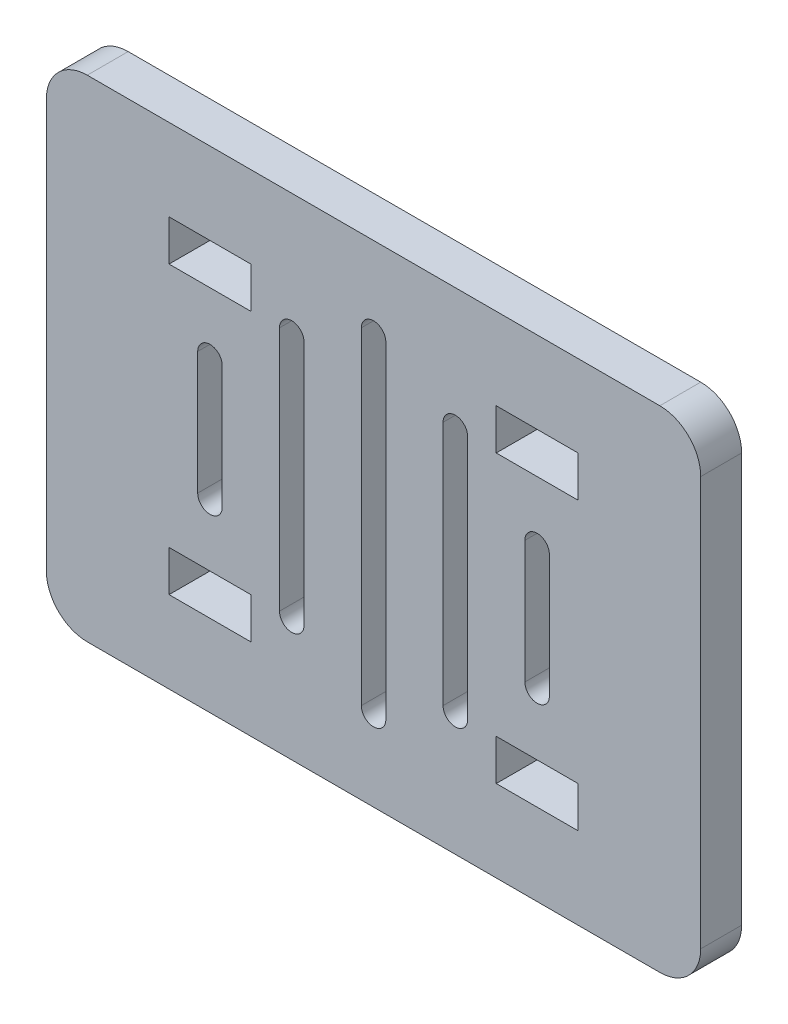
SolidWorks part; units mm, degrees
ref_plane "Front Plane" through (0, 0, 0) normal (1, 0, 0) x (0, 1, 0)
ref_plane "Top Plane" through (0, 0, 0) normal (0, 0, 1) x (0, 1, 0)
ref_plane "Right Plane" through (0, 0, 0) normal (0, 1, 0) x (-1, 0, 0)
sketch "Sketch1" plane through (0, 0, 0) normal (0, 0, 1) x (0, 1, 0)
  line L0 (0, 0) -> (0, 40) construction
  line L1 (0, -0.75) -> (0, 0)
  line L2 (-15, 0) -> (15, 0) construction
  line L3 (15, -5) -> (15, 5)
  line L4 (20, -5) -> (20, 5)
  line L5 (15, -5) -> (20, -5)
  line L6 (15, 5) -> (20, 5)
  line L7 (0, 20) -> (15, 20) construction
  line L8 (20, 45) -> (20, 35)
  line L9 (15, 45) -> (20, 45)
  line L10 (15, 45) -> (15, 35)
  line L11 (15, 35) -> (20, 35)
  line L12 (-15, 40) -> (15, 40) construction
  line L13 (-15, 5) -> (-20, 5)
  line L14 (-15, -5) -> (-20, -5)
  line L15 (-20, -5) -> (-20, 5)
  line L16 (-15, -5) -> (-15, 5)
  line L17 (-15, 35) -> (-20, 35)
  line L18 (-15, 45) -> (-15, 35)
  line L19 (-15, 45) -> (-20, 45)
  line L20 (-20, 45) -> (-20, 35)
  line L21 (0, 40) -> (0, 60) construction
  line L22 (0, 0) -> (0, -20)
  line L23 (30, 0) -> (30, -20)
  line L24 (30, 0) -> (30, 40)
  line L25 (30, 40) -> (30, 60)
  line L26 (-30, 0) -> (-30, -20)
  line L27 (-30, 0) -> (-30, 40)
  line L28 (-30, 40) -> (-30, 60)
  line L29 (30, -20) -> (-30, -20)
  line L30 (30, 60) -> (-30, 60)
  line L31 (7.5, 40) -> (-7.5, 40)
  line L32 (0, 40) -> (0, 30)
  line L33 (15, 30) -> (-15, 30)
  line L34 (0, 30) -> (0, 20)
  line L35 (20, 20) -> (-20, 20)
  line L36 (7.5, 0) -> (-7.5, 0)
  line L37 (15, 10) -> (-15, 10)
  line L38 (7.5, 41.5) -> (-7.5, 41.5)
  line L39 (15, 31.5) -> (-15, 31.5)
  line L40 (20, 21.5) -> (-20, 21.5)
  line L41 (15, 11.5) -> (-15, 11.5)
  line L42 (7.5, 1.5) -> (-7.5, 1.5)
  line L43 (7.5, 38.5) -> (-7.5, 38.5)
  line L44 (15, 28.5) -> (-15, 28.5)
  line L45 (20, 18.5) -> (-20, 18.5)
  line L46 (15, 8.5) -> (-15, 8.5)
  line L47 (7.5, -1.5) -> (-7.5, -1.5)
  arc A0 (7.5, 41.5) -> (7.5, 38.5) centre (7.5, 40) cw
  arc A1 (-7.5, 41.5) -> (-7.5, 38.5) centre (-7.5, 40) ccw
  arc A2 (15, 31.5) -> (15, 28.5) centre (15, 30) cw
  arc A3 (-15, 31.5) -> (-15, 28.5) centre (-15, 30) ccw
  arc A4 (20, 21.5) -> (20, 18.5) centre (20, 20) cw
  arc A5 (-20, 21.5) -> (-20, 18.5) centre (-20, 20) ccw
  arc A6 (15, 11.5) -> (15, 8.5) centre (15, 10) cw
  arc A7 (-15, 11.5) -> (-15, 8.5) centre (-15, 10) ccw
  arc A8 (7.5, 1.5) -> (7.5, -1.5) centre (7.5, 0) cw
  arc A9 (-7.5, 1.5) -> (-7.5, -1.5) centre (-7.5, 0) ccw
  point P4 (0, 0)
  point P10 (15, 0)
  point P19 (-15, 0)
  point P42 (0, 40)
  point P46 (0, 30)
  point P49 (0, 20)
  dimension "D1" = 15
  dimension "D2" = 10
  dimension "D3" = 40
  dimension "D4" = 5
  dimension "D5" = 20
  dimension "D6" = 20
  dimension "D7" = 15
  dimension "D8" = 10
  dimension "D9" = 30
  dimension "D10" = 40
  dimension "D11" = 30
  dimension "D12" = 30
extrude "Boss-Extrude1" add sketch "Sketch1" along normal mid plane 5
fillet "Fillet1" radius 5 4 edges at (-60, -30, 0) (-60, 30, 0) (20, 30, 0) (20, -30, 0)
